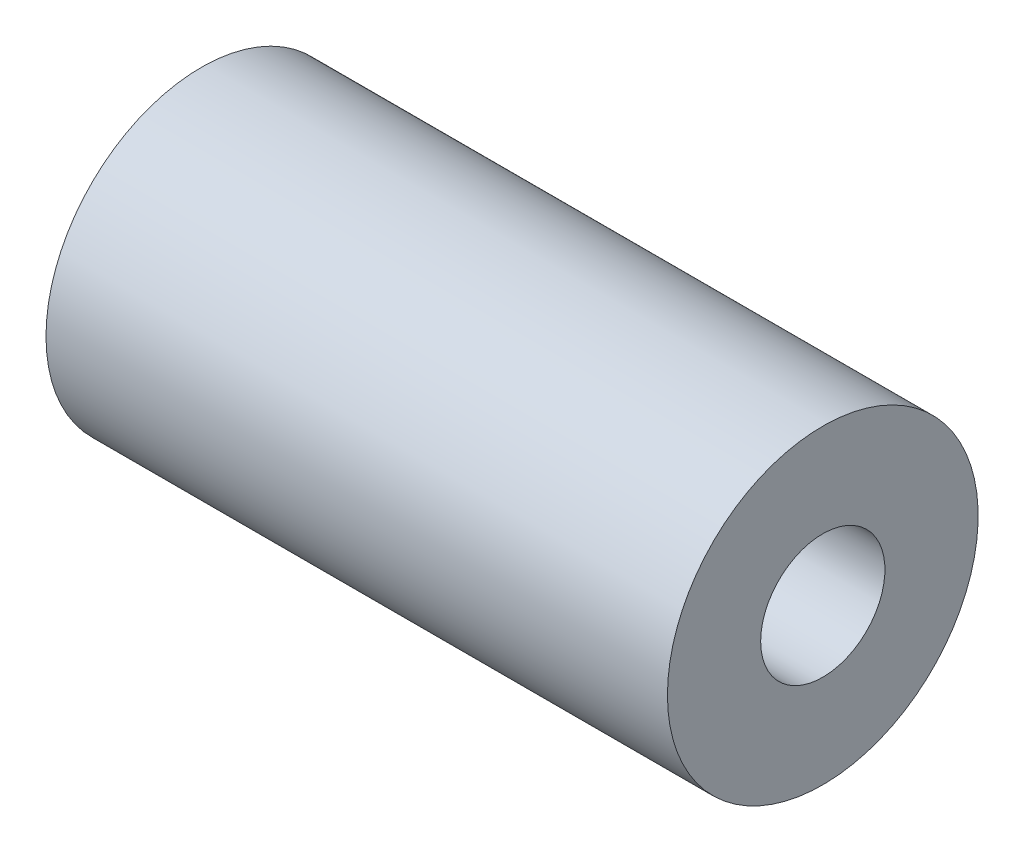
SolidWorks part; units mm, degrees
ref_plane "Plan de face" through (0, 0, 0) normal (0, 0, 1) x (1, 0, 0)
ref_plane "Plan de dessus" through (0, 0, 0) normal (0, 1, 0) x (1, 0, 0)
ref_plane "Plan de droite" through (0, 0, 0) normal (1, 0, 0) x (0, 0, -1)
sketch "Esquisse1" plane through (0, 0, 0) normal (0, 0, 1) x (1, 0, 0)
  line L0 (-26.9454, 0) -> (84.9962, 0) construction
  line L1 (0, 0) -> (15, 0)
  line L2 (0, 0) -> (0, 7.5)
  line L3 (0, 7.5) -> (15, 7.5)
  line L4 (15, 0) -> (15, 7.5)
  line L6 (0, 0) -> (15, 0)
  line L7 (0, 0) -> (0, 2.5)
  line L8 (0, 2.5) -> (15, 2.5)
  line L9 (15, 0) -> (15, 2.5)
  line L10 (15, 2.5) -> (30, 2.5)
  line L11 (15, 2.5) -> (15, 0)
  line L12 (15, 0) -> (30, 0)
  line L13 (30, 2.5) -> (30, 0)
  line L14 (15, 7.5) -> (30, 7.5)
  line L15 (15, 7.5) -> (15, 2.5)
  line L16 (15, 2.5) -> (30, 2.5)
  line L17 (30, 7.5) -> (30, 2.5)
  line L18 (15, 0) -> (30, 0)
  line L19 (15, 0) -> (15, 3)
  line L20 (15, 3) -> (30, 3)
  line L21 (30, 0) -> (30, 3)
  dimension "D1" = 2.5
  dimension "D2" = 7.5
  dimension "D3" = 15
  dimension "D4" = 15
  dimension "D5" = 3
revolve "Révolution1" add sketch "Esquisse1" angle 360 about L0
sketch "Esquisse2" plane through (0, 0, 0) normal (0, 1, 0) x (1, 0, 0)
  line L0 (0, 7.5) -> (0, -7.5) construction
  line L1 (30, -7.5) -> (30, 7.5) construction
  circle A0 centre (7, 0) radius 2
  circle A1 centre (23, 0) radius 2
  dimension "D1" = 4
  dimension "D2" = 4
  dimension "D3" = 7
  dimension "D4" = 7
extrude "Enlèv. mat.-Extru.1" cut sketch "Esquisse2" against normal through all
